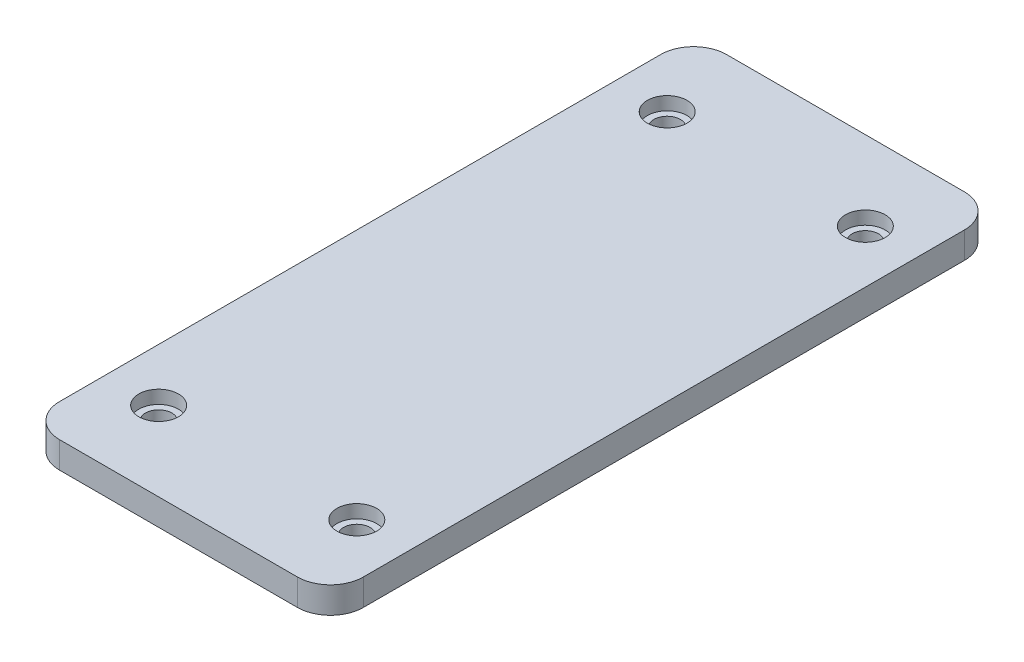
SolidWorks part; units mm, degrees
material "ABS"
ref_plane "Alzado" through (0, 0, 0) normal (0, 0, 1) x (1, 0, 0)
ref_plane "Planta" through (0, 0, 0) normal (0, 1, 0) x (1, 0, 0)
ref_plane "Vista lateral" through (0, 0, 0) normal (1, 0, 0) x (0, 0, -1)
sketch "Croquis1" plane through (0, 0, 0) normal (0, 1, 0) x (1, 0, 0)
  line L1 (-23, 50.5) -> (23, 50.5)
  line L2 (-23, 50.5) -> (-23, -50.5)
  line L3 (-23, -50.5) -> (23, -50.5)
  line L4 (23, 50.5) -> (23, -50.5)
  line L5 (-23, 50.5) -> (23, -50.5) construction
  line L6 (-23, -50.5) -> (23, 50.5) construction
  point P0 (0, 0)
  dimension "D1" = 46
  dimension "D2" = 101
extrude "Saliente-Extruir2" add sketch "Croquis1" along normal blind 4
sketch "Croquis2" plane through (0, 4, 0) normal (0, 1, 0) x (1, 0, 0)
  line L0 (23, 50.5) -> (-23, 50.5) construction
  line L1 (-23, 50.5) -> (-23, -50.5) construction
  line L2 (0, 50.5) -> (0, 33.1785)
  line L3 (0, 0) -> (15.3995, 0)
  circle A0 centre (-15, 38.5) radius 2
  circle A1 centre (15, 38.5) radius 2
  circle A2 centre (15, -38.5) radius 2
  circle A3 centre (-15, -38.5) radius 2
  dimension "D1" = 12
  dimension "D2" = 8
extrude "Cortar-Extruir3" cut sketch "Croquis2" against normal blind 36 contours A0 | A1 | A3 | A2
sketch "Croquis4" plane through (0, 4, 0) normal (0, 1, 0) x (1, 0, 0)
  circle A0 centre (-15, -38.5) radius 3
  circle A1 centre (15, -38.5) radius 3
  circle A2 centre (-15, 38.5) radius 3
  circle A3 centre (15, 38.5) radius 3
extrude "Cortar-Extruir4" cut sketch "Croquis4" against normal blind 2
fillet "Redondeo1" radius 5 4 edges at (-23, 2, -50.5) (23, 2, -50.5) (23, 2, 50.5) (-23, 2, 50.5)
